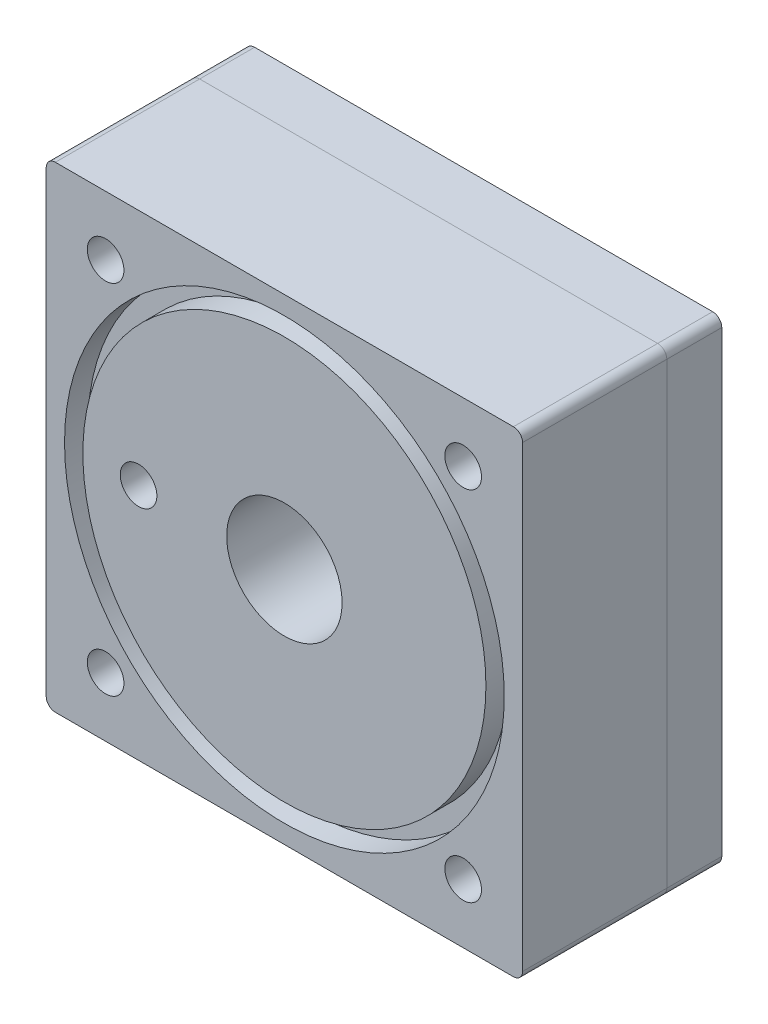
SolidWorks part; units mm, degrees
ref_plane "Front Plane" through (0, 0, 0) normal (0, 0, 1) x (1, 0, 0)
ref_plane "Top Plane" through (0, 0, 0) normal (0, 1, 0) x (1, 0, 0)
ref_plane "Right Plane" through (0, 0, 0) normal (1, 0, 0) x (0, 0, -1)
sketch "Sketch1" plane through (0, 0, 0) normal (0, 0, 1) x (1, 0, 0)
  line L1 (82.55, -82.55) -> (-82.55, -82.55)
  line L2 (82.55, -82.55) -> (82.55, 82.55)
  line L3 (82.55, 82.55) -> (-82.55, 82.55)
  line L4 (-82.55, -82.55) -> (-82.55, 82.55)
  line L5 (82.55, -82.55) -> (-82.55, 82.55) construction
  line L6 (82.55, 82.55) -> (-82.55, -82.55) construction
  point P0 (0, 0)
  dimension "D1" = 165.1
extrude "Boss-Extrude1" add sketch "Sketch1" along normal blind 50
sketch "Sketch2" plane through (0, 0, 0) normal (0, 0, -1) x (-1, 0, 0)
  circle A0 centre (0, 0) radius 40
  dimension "D1" = 80
extrude "Boss-Extrude2" add sketch "Sketch2" along normal blind 50.8
sketch "Sketch4" plane through (0, 0, -50.8) normal (0, 0, -1) x (-1, 0, 0)
  circle A0 centre (0, 0) radius 32
extrude "Cut-Extrude1" cut sketch "Sketch4" against normal blind 28
sketch "Sketch5" plane through (0, 0, -22.8) normal (0, 0, -1) x (-1, 0, 0)
  circle A0 centre (0, 0) radius 30
extrude "Cut-Extrude2" cut sketch "Sketch5" against normal blind 22
fillet "Fillet1" radius 3.175 4 edges at (-82.55, -82.55, 25) (82.55, 82.55, 25) (-82.55, 82.55, 25) (82.55, -82.55, 25)
sketch "Sketch6" plane through (0, 0, 50) normal (0, 0, 1) x (1, 0, 0)
  circle A0 centre (0, 0) radius 20
  dimension "D1" = 40
extrude "Cut-Extrude4" cut sketch "Sketch6" against normal blind 40
sketch "Sketch7" plane through (0, 0, 50) normal (0, 0, 1) x (1, 0, 0)
  circle A0 centre (0, 0) radius 76.2
  circle A1 centre (0, 0) radius 69.85
  dimension "D1" = 152.4
  dimension "D2" = 139.7
extrude "Cut-Extrude5" cut sketch "Sketch7" against normal blind 8
sketch "Sketch8" plane through (-82.55, 0, 0) normal (-1, 0, 0) x (0, 0, 1)
  line L0 (25, -79.375) -> (25, 79.375) construction
  line L1 (0, -79.375) -> (50, -79.375) construction
  line L2 (50, 79.375) -> (0, 79.375) construction
hole_wizard "1/2-14 NPSM Tapped Hole1" positions "Sketch9" profile "Sketch10" tap size "1/2-14 NPSM" standard "ANSI Inch"
sketch "Sketch9" plane through (-82.55, 0, 0) normal (-1, 0, 0) x (0, 0, 1)
  line L0 (25, -79.375) -> (25, 79.375) construction
  point P0 (25, 0)
sketch "Sketch10" plane through (-82.55, 0, 25) normal (0, 1, 0) x (0, 0, 1)
  line L0 (0, 0) -> (0, 52.9403)
  line L1 (0, 52.9403) -> (9.4869, 47.24)
  line L2 (9.4869, 47.24) -> (9.4869, 0)
  line L5 (9.4869, 0) -> (0, 0)
  line L10 (0, 52.9403) -> (-9.4869, 47.24) construction
  line L11 (0, -6.35) -> (0, 107.95) construction
  dimension "Tap Drill Dia." = 18.9738
  dimension "Tap Drill Depth" = 47.24
  dimension "Drill Angle" = 118
cosmetic thread "Hole Thread1" parameters "D1"=41.81, "D2"=20.9042
sketch "Sketch11" plane through (0, 0, 50) normal (0, 0, 1) x (1, 0, 0)
  line L0 (-82.55, -79.375) -> (-82.55, 79.375) construction
  circle A0 centre (-50.55, 0) radius 6.35
  point P4 (0, 0)
  point P6 (0, 0)
  dimension "D2" = 12.7
  dimension "D1" = 32
extrude "Cut-Extrude6" cut sketch "Sketch11" against normal blind 25
sketch "Sketch12" plane through (0, 0, 50) normal (0, 0, 1) x (1, 0, 0)
  line L1 (61.9638, -61.9638) -> (-61.9638, -61.9638) construction
  line L2 (61.9638, -61.9638) -> (61.9638, 61.9638) construction
  line L3 (61.9638, 61.9638) -> (-61.9638, 61.9638) construction
  line L4 (-61.9638, -61.9638) -> (-61.9638, 61.9638) construction
  line L5 (61.9638, -61.9638) -> (-61.9638, 61.9638) construction
  line L6 (61.9638, 61.9638) -> (-61.9638, -61.9638) construction
  circle A0 centre (0, 0) radius 87.63 construction
  circle A1 centre (-61.9638, 61.9638) radius 6.35
  circle A2 centre (61.9638, 61.9638) radius 6.35
  circle A3 centre (61.9638, -61.9638) radius 6.35
  circle A4 centre (-61.9638, -61.9638) radius 6.35
  dimension "D1" = 175.26
  dimension "D2" = 12.7
  dimension "D3" = 4
extrude "Cut-Extrude7" cut sketch "Sketch12" against normal through all
sketch "Sketch13" plane through (0, 0, 0) normal (0, 0, -1) x (-1, 0, 0)
  line L0 (-79.375, 82.55) -> (79.375, 82.55) construction
  line L1 (-82.55, -79.375) -> (-82.55, 79.375) construction
  line L2 (79.375, -82.55) -> (-79.375, -82.55) construction
  line L3 (82.55, 79.375) -> (82.55, -79.375) construction
  line L4 (-79.375, 82.55) -> (79.375, 82.55)
  line L5 (-82.55, -79.375) -> (-82.55, 79.375)
  line L6 (79.375, -82.55) -> (-79.375, -82.55)
  line L7 (82.55, 79.375) -> (82.55, -79.375)
  arc A0 (82.55, 79.375) -> (79.375, 82.55) centre (79.375, 79.375) ccw construction
  circle A1 centre (0, 0) radius 40
  circle A2 centre (0, 0) radius 40
  circle A3 centre (61.9638, 61.9638) radius 6.35
  circle A4 centre (61.9638, 61.9638) radius 6.35
  circle A5 centre (-61.9638, 61.9638) radius 6.35
  circle A6 centre (-61.9638, 61.9638) radius 6.35
  circle A7 centre (-61.9638, -61.9638) radius 6.35
  circle A8 centre (-61.9638, -61.9638) radius 6.35
  circle A9 centre (61.9638, -61.9638) radius 6.35
  circle A10 centre (61.9638, -61.9638) radius 6.35
  arc A11 (-79.375, 82.55) -> (-82.55, 79.375) centre (-79.375, 79.375) ccw construction
  arc A12 (-82.55, -79.375) -> (-79.375, -82.55) centre (-79.375, -79.375) ccw construction
  arc A13 (79.375, -82.55) -> (82.55, -79.375) centre (79.375, -79.375) ccw construction
  arc A14 (82.55, 79.375) -> (79.375, 82.55) centre (79.375, 79.375) ccw
  arc A15 (-79.375, 82.55) -> (-82.55, 79.375) centre (-79.375, 79.375) ccw
  arc A16 (-82.55, -79.375) -> (-79.375, -82.55) centre (-79.375, -79.375) ccw
  arc A17 (79.375, -82.55) -> (82.55, -79.375) centre (79.375, -79.375) ccw
  dimension "D1" = 0
  dimension "D2" = 0
  dimension "D3" = 0
  dimension "D4" = 0
  dimension "D5" = 0
extrude "Boss-Extrude3" add sketch "Sketch13" along normal blind 19.05 separate body
